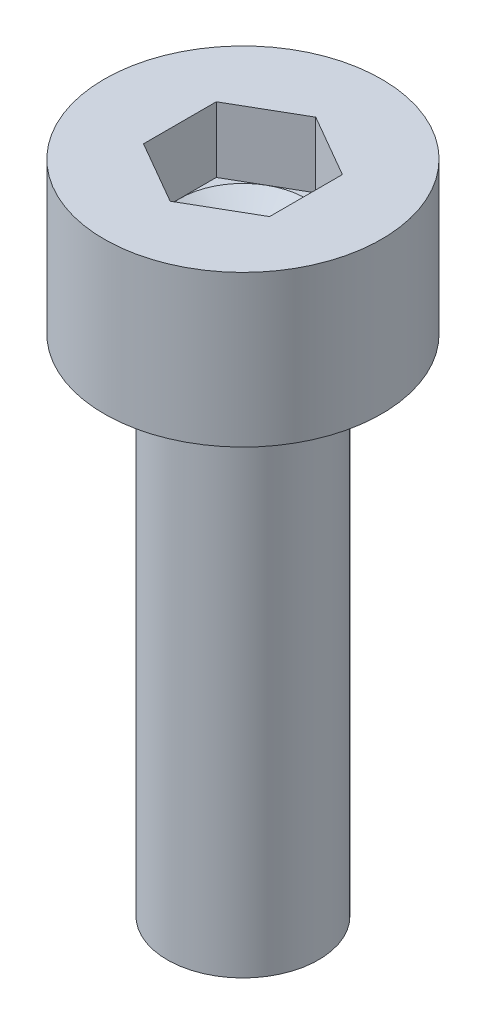
SolidWorks part; units mm, degrees
ref_plane "Front Plane" through (0, 0, 0) normal (0, 0, 1) x (1, 0, 0)
ref_plane "Top Plane" through (0, 0, 0) normal (0, 1, 0) x (1, 0, 0)
ref_plane "Right Plane" through (0, 0, 0) normal (1, 0, 0) x (0, 0, -1)
sketch "Sketch1" plane through (0, 0, 0) normal (0, 0, 1) x (1, 0, 0)
  line L0 (0, 0) -> (2.75, 0)
  line L1 (2.75, 0) -> (2.75, -3)
  line L2 (2.75, -3) -> (1.5, -3)
  line L3 (1.5, -3) -> (1.5, -13)
  line L4 (1.5, -13) -> (0, -13)
  line L5 (0, -13) -> (0, 0)
  line L7 (0, 0) -> (0, -13) construction
  dimension "CS_A" = 5.5
  dimension "CS_L" = 10
  dimension "CS_M" = 3
  dimension "CS_E" = 3
revolve "Revolve1" add sketch "Sketch1" angle 360 about L7
cosmetic thread "Cosmetic Thread1" parameters "CS_D_s"=2.459
sketch "Sketch2" plane through (0, 0, 0) normal (0, 0, 1) x (1, 0, 0)
  line L0 (1.25, 0) -> (1.25, -1.3)
  line L1 (1.25, -1.3) -> (0, -2.0217)
  line L2 (0, -2.0217) -> (0, 0)
  line L3 (0, 0) -> (1.25, 0)
  line L4 (0, 0) -> (0, -2.0217) construction
  dimension "D1" = 60
  dimension "CS_B" = 2.5
  dimension "CS_T_s" = 1.3
revolve "Cut-Revolve1" cut sketch "Sketch2" angle 360 about L4
sketch "Sketch3" plane through (0, 0, 0) normal (0, 1, 0) x (1, 0, 0)
  line L1 (0, 1.4434) -> (-1.25, 0.7217)
  line L2 (-1.25, 0.7217) -> (-1.25, -0.7217)
  line L3 (-1.25, -0.7217) -> (0, -1.4434)
  line L4 (0, -1.4434) -> (1.25, -0.7217)
  line L5 (1.25, -0.7217) -> (1.25, 0.7217)
  line L6 (1.25, 0.7217) -> (0, 1.4434)
  circle A0 centre (0, 0) radius 1.25 construction
extrude "Cut-Extrude1" cut sketch "Sketch3" against normal blind 1.3
